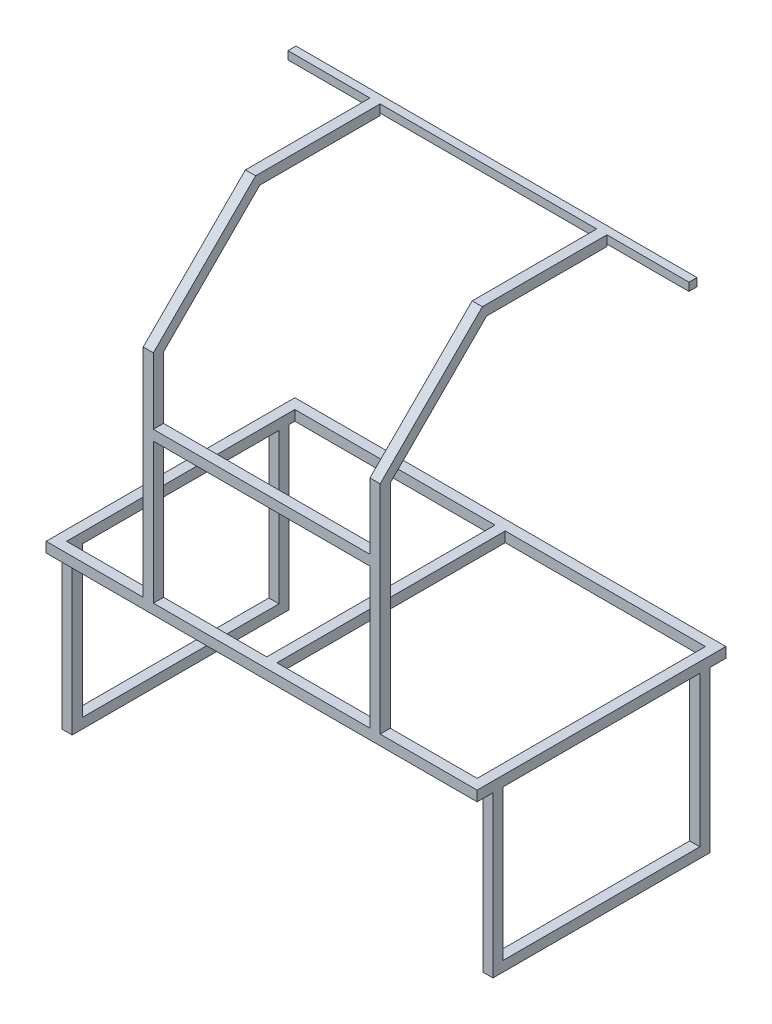
SolidWorks part; units mm, degrees
ref_plane "Front Plane" through (0, 0, 0) normal (0, 0, 1) x (1, 0, 0)
ref_plane "Top Plane" through (0, 0, 0) normal (0, 1, 0) x (1, 0, 0)
ref_plane "Right Plane" through (0, 0, 0) normal (1, 0, 0) x (0, 0, -1)
sketch "Sketch1" plane through (0, 0, 0) normal (0, 1, 0) x (1, 0, 0)
  line L0 (-511.9, 284.6) -> (511.9, 284.6)
  line L1 (-537.3, -310) -> (537.3, -310)
  line L2 (-537.3, -310) -> (-537.3, 310)
  line L3 (-537.3, 310) -> (537.3, 310)
  line L4 (537.3, -310) -> (537.3, 310)
  line L5 (-537.3, -310) -> (537.3, 310) construction
  line L6 (-537.3, 310) -> (537.3, -310) construction
  line L7 (511.9, -284.6) -> (511.9, 284.6)
  line L8 (-511.9, -284.6) -> (511.9, -284.6)
  line L9 (-511.9, -284.6) -> (-511.9, 284.6)
  point P0 (0, 0)
  dimension "D1" = 1074.6
  dimension "D2" = 620
  dimension "D3" = 25.4
extrude "Boss-Extrude1" add sketch "Sketch1" along normal blind 25.4
sketch "Sketch2" plane through (0, 0, 0) normal (0, -1, 0) x (1, 0, 0)
  line L0 (0, 310) -> (0, -310) construction
  line L1 (-537.3, 310) -> (537.3, 310) construction
  line L2 (537.3, -310) -> (-537.3, -310) construction
  line L3 (-537.3, -310) -> (-537.3, 310) construction
  line L4 (-537.3, 270.6) -> (-511.9, 270.6)
  line L5 (-537.3, 270.6) -> (-537.3, 245.2)
  line L6 (-537.3, 245.2) -> (-511.9, 245.2)
  line L7 (-511.9, 270.6) -> (-511.9, 245.2)
  line L8 (-511.9, -284.6) -> (-511.9, 284.6) construction
  line L9 (-511.9, 284.6) -> (511.9, 284.6) construction
  line L10 (511.9, -284.6) -> (-511.9, -284.6) construction
  line L11 (-511.9, -245.2) -> (-537.3, -245.2)
  line L12 (-511.9, -245.2) -> (-511.9, -270.6)
  line L13 (-511.9, -270.6) -> (-537.3, -270.6)
  line L14 (-537.3, -245.2) -> (-537.3, -270.6)
  line L15 (511.9, 270.6) -> (511.9, 245.2)
  line L16 (537.3, 245.2) -> (511.9, 245.2)
  line L17 (537.3, 270.6) -> (537.3, 245.2)
  line L18 (537.3, 270.6) -> (511.9, 270.6)
  line L19 (537.3, -245.2) -> (537.3, -270.6)
  line L20 (511.9, -270.6) -> (537.3, -270.6)
  line L21 (511.9, -245.2) -> (511.9, -270.6)
  line L22 (511.9, -245.2) -> (537.3, -245.2)
  dimension "D1" = 25.4
  dimension "D2" = 14
  dimension "D3" = 14
  dimension "D4" = 25.4
  dimension "D5" = 25.4
extrude "Boss-Extrude2" add sketch "Sketch2" along normal blind 400
sketch "Sketch3" plane through (0, 0, 245.2) normal (0, 0, -1) x (-1, 0, 0)
  line L0 (511.9, -400) -> (511.9, 0) construction
  line L1 (537.3, -400) -> (511.9, -400)
  line L2 (537.3, -400) -> (537.3, -374.6)
  line L3 (537.3, -374.6) -> (511.9, -374.6)
  line L4 (511.9, -400) -> (511.9, -374.6)
  line L5 (-537.3, -400) -> (-537.3, 0) construction
  line L6 (-511.9, -400) -> (-537.3, -400)
  line L7 (-511.9, -400) -> (-511.9, -374.6)
  line L8 (-511.9, -374.6) -> (-537.3, -374.6)
  line L9 (-537.3, -400) -> (-537.3, -374.6)
  dimension "D1" = 25.4
  dimension "D2" = 25.4
extrude "Boss-Extrude3" add sketch "Sketch3" along normal up to surface (490.4 mm away) up to face at (524.6, -200, -245.2)
sketch "Sketch4" plane through (0, 25.4, 0) normal (0, 1, 0) x (1, 0, 0)
  line L0 (0, -310) -> (0, 310) construction
  line L1 (-537.3, -310) -> (537.3, -310) construction
  line L2 (537.3, 310) -> (-537.3, 310) construction
  line L4 (-511.9, -284.6) -> (511.9, -284.6) construction
  line L5 (-12.7, 284.6) -> (12.7, 284.6)
  line L6 (-12.7, 284.6) -> (-12.7, -284.6)
  line L7 (-12.7, -284.6) -> (12.7, -284.6)
  line L10 (12.7, 284.6) -> (12.7, -284.6)
  line L11 (-12.7, 284.6) -> (12.7, -284.6) construction
  line L12 (-12.7, -284.6) -> (12.7, 284.6) construction
  point P6 (0, 0)
  dimension "D1" = 25.4
sketch "Sketch5" plane through (0, 25.4, 0) normal (0, 1, 0) x (1, 0, 0)
  line L0 (0, -310) -> (0, -284.6) construction
  line L1 (-537.3, -310) -> (537.3, -310) construction
  line L2 (-511.9, -284.6) -> (511.9, -284.6) construction
  line L4 (295.4, -310) -> (270, -310)
  line L5 (295.4, -310) -> (295.4, -284.6)
  line L6 (295.4, -284.6) -> (270, -284.6)
  line L7 (270, -310) -> (270, -284.6)
  dimension "D1" = 25.4
  dimension "D2" = 270
extrude "Boss-Extrude5" add sketch "Sketch5" along normal blind 50
extrude "Boss-Extrude6" add sketch "Sketch4" against normal blind 25.4
sketch "Sketch8" plane through (295.4, 0, 0) normal (1, 0, 0) x (0, 0, -1)
  line L0 (-284.6, 75.4) -> (-284.6, 555.4)
  line L1 (-284.6, 555.4) -> (-44.6, 795.4)
  line L2 (-44.6, 795.4) -> (255.4, 795.4)
  line L3 (-310, 25.4) -> (310, 25.4) construction
  line L4 (-310, 75.4) -> (-310, 565.921)
  line L5 (-310, 565.921) -> (-55.121, 820.8)
  line L6 (-55.121, 820.8) -> (255.4, 820.8)
  line L7 (255.4, 820.8) -> (255.4, 795.4)
  line L8 (-284.6, 75.4) -> (-310, 75.4)
  dimension "D1" = 530
  dimension "D2" = 770
  dimension "D3" = 135
  dimension "D4" = 300
  dimension "D5" = 25.4
extrude "Boss-Extrude7" add sketch "Sketch8" against normal blind 25.4
sketch "Sketch9" plane through (270, 0, 0) normal (-1, 0, 0) x (0, 0, 1)
  line L0 (284.6, 555.4) -> (284.6, 25.4) construction
  line L1 (284.6, 400.8) -> (310, 400.8)
  line L2 (284.6, 400.8) -> (284.6, 375.4)
  line L3 (284.6, 375.4) -> (310, 375.4)
  line L4 (310, 400.8) -> (310, 375.4)
  line L5 (310, 565.921) -> (310, 25.4) construction
  line L6 (-310, 25.4) -> (310, 25.4) construction
  dimension "D1" = 25.4
  dimension "D2" = 350
extrude "Boss-Extrude8" add sketch "Sketch9" along normal blind 270
mirror "Mirror1" about plane through (0, 0, 0) normal (-1, 0, 0) of "Boss-Extrude7", "Boss-Extrude1", "Boss-Extrude8", "Boss-Extrude5"
sketch "Sketch10" plane through (0, 820.8, 0) normal (0, 1, 0) x (1, 0, 0)
  line L0 (0, 0) -> (0, 378.0797) construction
  line L1 (270, 255.4) -> (295.4, 255.4) construction
  line L2 (-500, 275.4) -> (500, 275.4)
  line L3 (-500, 275.4) -> (-500, 255.4)
  line L4 (-500, 255.4) -> (500, 255.4)
  line L5 (500, 275.4) -> (500, 255.4)
  line L6 (-500, 275.4) -> (500, 255.4) construction
  line L7 (-500, 255.4) -> (500, 275.4) construction
  point P3 (0, 265.4)
  dimension "D1" = 1000
  dimension "D2" = 20
extrude "Boss-Extrude9" add sketch "Sketch10" against normal blind 20
